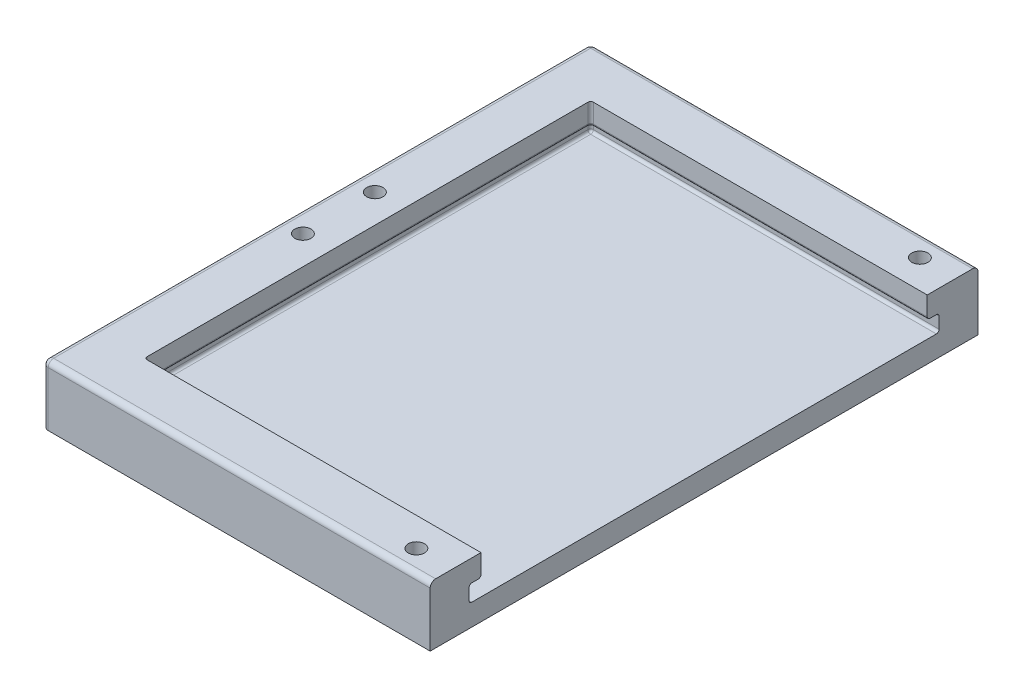
SolidWorks part; units mm, degrees
ref_plane "Front Plane" through (0, 0, 0) normal (0, 0, 1) x (1, 0, 0)
ref_plane "Top Plane" through (0, 0, 0) normal (0, 1, 0) x (1, 0, 0)
ref_plane "Right Plane" through (0, 0, 0) normal (1, 0, 0) x (0, 0, -1)
sketch "Sketch1" plane through (0, 0, 0) normal (0, 1, 0) x (1, 0, 0)
  line L1 (-35.85, 50.7) -> (35.85, 50.7)
  line L2 (-35.85, 50.7) -> (-35.85, -50.7)
  line L3 (-35.85, -50.7) -> (35.85, -50.7)
  line L4 (35.85, 50.7) -> (35.85, -50.7)
  line L5 (-35.85, 50.7) -> (35.85, -50.7) construction
  line L6 (-35.85, -50.7) -> (35.85, 50.7) construction
  point P0 (0, 0)
  dimension "D1" = 71.7
  dimension "D2" = 101.4
extrude "Boss-Extrude1" add sketch "Sketch1" along normal blind 11.1 contours L1 L4 L3 L2
sketch "Sketch5" plane through (35.85, 0, 0) normal (1, 0, 0) x (0, 0, -1)
  line L0 (-41.3, 18.3639) -> (-41.3, 7.1)
  line L1 (-41.3, 7.1) -> (-43.5, 7.1)
  line L2 (-43.5, 7.1) -> (-43.5, 4)
  line L3 (-43.5, 4) -> (43.5, 4)
  line L4 (0, 0) -> (0, 18.3639) construction
  line L5 (50.7, 0) -> (-50.7, 0) construction
  line L7 (-41.3, 18.3639) -> (41.3, 18.3639)
  line L8 (43.5, 7.1) -> (43.5, 4)
  line L9 (41.3, 7.1) -> (43.5, 7.1)
  line L10 (41.3, 18.3639) -> (41.3, 7.1)
  point P9 (0, 4)
  dimension "D1" = 87
  dimension "D2" = 3.1
  dimension "D3" = 4
  dimension "D4" = 2.2
extrude "Cut-Extrude1" cut sketch "Sketch5" against normal blind 62.3
sketch "Sketch6" plane through (-26.45, 0, 0) normal (1, 0, 0) x (0, 0, -1)
  line L0 (-43.5, 7.1) -> (-43.5, 4)
  line L1 (-43.5, 4) -> (43.5, 4)
  line L2 (43.5, 4) -> (43.5, 7.1) construction
  line L3 (43.5, 4) -> (43.5, 7.1)
  line L4 (43.5, 7.1) -> (-43.5, 7.1)
extrude "Cut-Extrude2" cut sketch "Sketch6" against normal blind 2.2
fillet "Fillet1" radius 0.5 13 edges at (3.6, 7.1, -43.5) (3.6, 4, -43.5) (-28.65, 4, 0) (3.6, 4, 43.5) (-28.65, 5.55, 43.5) (-28.65, 5.55, -43.5) (-26.45, 9.1, -41.3) (-26.45, 9.1, 41.3) (3.6, 7.1, 43.5) (4.7, 7.1, 41.3) (4.7, 7.1, -41.3) (-26.45, 7.1, 0) (-28.65, 7.1, 0)
fillet "Fillet2" radius 1 5 edges at (-35.85, 5.55, -50.7) (-35.85, 5.55, 50.7) (0, 11.1, -50.7) (0, 11.1, 50.7) (-35.85, 11.1, 0)
sketch "Sketch7" plane through (0, 11.1, 0) normal (0, 1, 0) x (1, 0, 0)
  line L0 (-35.85, 0) -> (0, 0) construction
  line L1 (-35.85, 50.7) -> (-35.85, -50.7) construction
  line L2 (-34.85, -6.6579) -> (-28.65, -6.6579) construction
  line L3 (-34.85, 49.7) -> (-34.85, -49.7) construction
  circle A0 centre (-31.75, -6.6579) radius 1.5
  circle A1 centre (-31.75, 6.6579) radius 1.5
  dimension "D1" = 3
  dimension "D2" = 6.6579
  dimension "D3" = 6.2
extrude "Cut-Extrude3" cut sketch "Sketch7" against normal blind 4
sketch "Sketch8" plane through (0, 11.1, 0) normal (0, 1, 0) x (1, 0, 0)
  line L0 (35.85, -41.3) -> (35.85, -49.7) construction
  line L1 (29.1921, -49.7) -> (29.1921, -43.5) construction
  line L4 (0, 0) -> (-35.85, 0) construction
  line L5 (-35.85, 50.7) -> (-35.85, -50.7) construction
  line L6 (-34.85, -49.7) -> (35.85, -49.7) construction
  circle A0 centre (29.1921, -46.6) radius 1.5
  circle A1 centre (29.1921, 46.6) radius 1.5
  dimension "D1" = 3
  dimension "D2" = 6.6579
  dimension "D3" = 6.2
extrude "Cut-Extrude4" cut sketch "Sketch8" against normal up to surface (4 mm away) up to face at (-1.9114, 7.1, 0)
